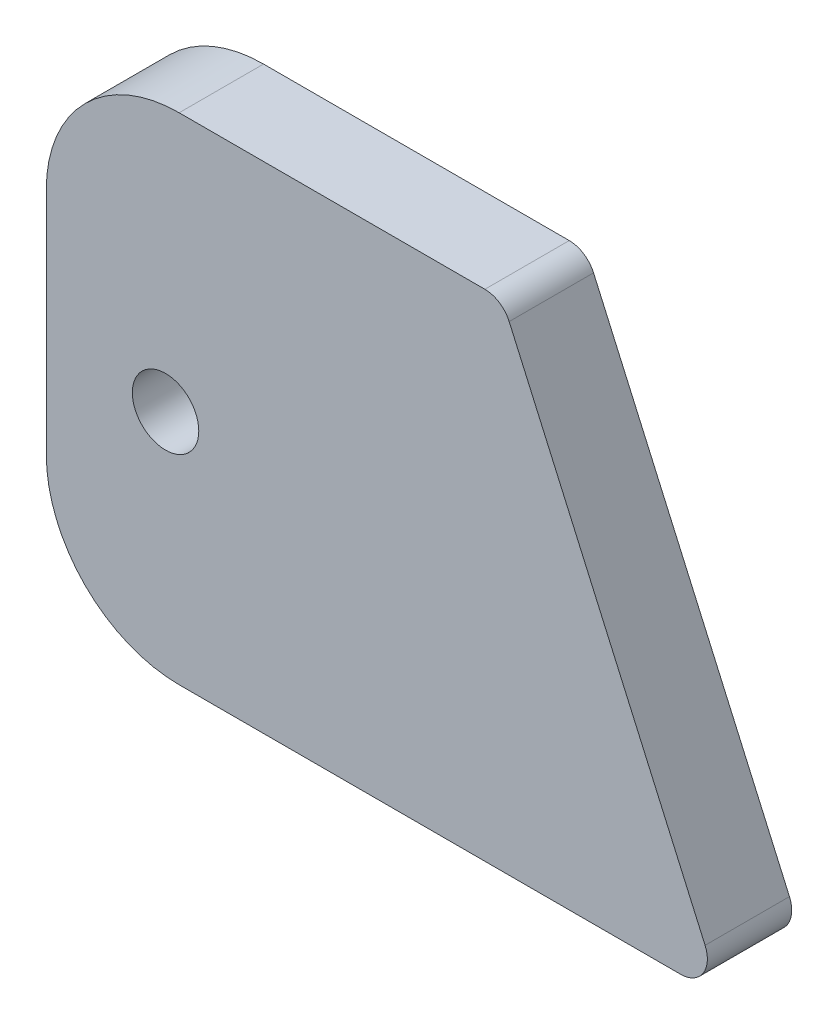
SolidWorks part; units mm, degrees
ref_plane "Front Plane" through (0, 0, 0) normal (0, 0, 1) x (1, 0, 0)
ref_plane "Top Plane" through (0, 0, 0) normal (0, 1, 0) x (1, 0, 0)
ref_plane "Right Plane" through (0, 0, 0) normal (1, 0, 0) x (0, 0, -1)
sketch "Sketch1" plane through (0, 0, 0) normal (0, 0, 1) x (1, 0, 0)
  line L2 (-11.8154, 9.3209) -> (-11.8154, -9.3209)
  line L9 (-11.8154, -9.3209) -> (12.9415, -9.3209)
  line L10 (12.9415, -9.3209) -> (4.6833, 9.3209) construction
  line L11 (4.6833, 9.3209) -> (-11.8154, 9.3209)
  line L13 (4.6833, 9.3209) -> (5.3397, 9.3209)
  line L14 (5.3397, 9.3209) -> (13.598, -9.3209)
  line L15 (13.598, -9.3209) -> (12.9415, -9.3209)
  dimension "D1" = 24.7569
  dimension "D2" = 9.3209
  dimension "D3" = 11.8154
  dimension "D4" = 18.6418
  dimension "D5" = 66.107
  dimension "D6" = 0.6565
extrude "Boss-Extrude1" add sketch "Sketch1" along normal mid plane 3.175
fillet "Fillet1" radius 1 2 edges at (13.598, -9.3209, 0) (5.3397, 9.3209, 0)
fillet "Fillet2" radius 5 2 edges at (-11.8154, 9.3209, 0) (-11.8154, -9.3209, 0)
sketch "Sketch2" plane through (0, 0, 1.5875) normal (0, 0, 1) x (1, 0, 0)
  circle A2 centre (-7.3275, -0.6791) radius 1.25
  dimension "D1" = 7.3275
  dimension "D3" = 2.5
  dimension "D2" = 0.6791
extrude "Cut-Extrude1" cut sketch "Sketch2" against normal through all
